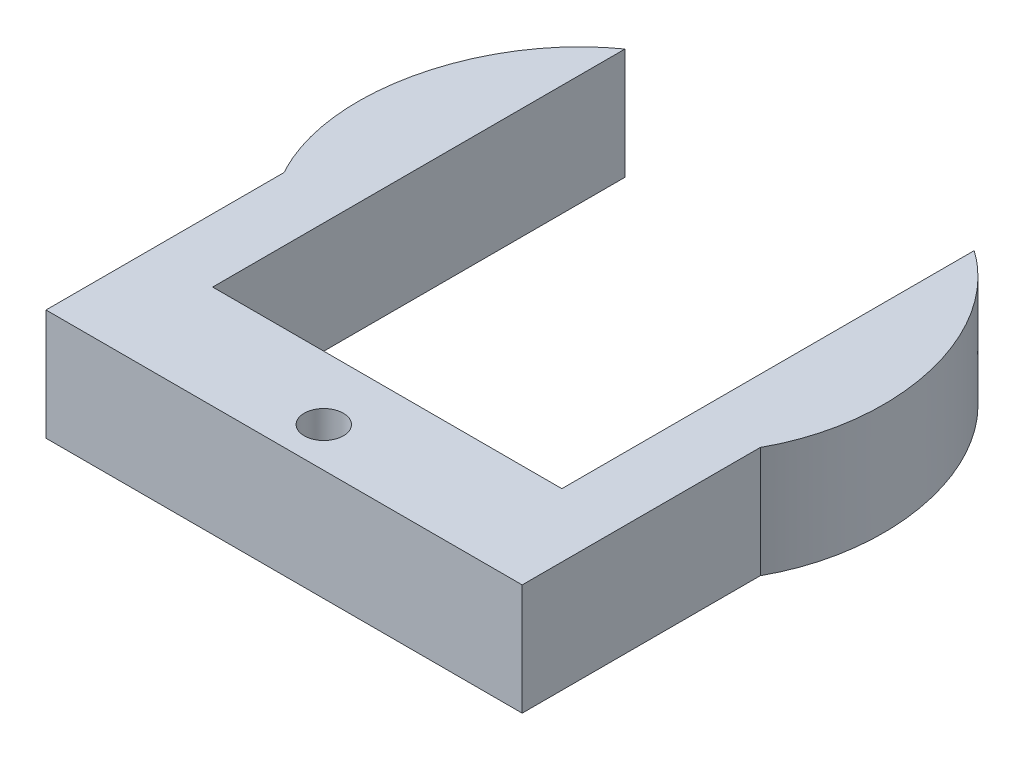
SolidWorks part; units mm, degrees
ref_plane "Front Plane" through (0, 0, 0) normal (0, 0, 1) x (1, 0, 0)
ref_plane "Top Plane" through (0, 0, 0) normal (0, 1, 0) x (1, 0, 0)
ref_plane "Right Plane" through (0, 0, 0) normal (1, 0, 0) x (0, 0, -1)
sketch "Sketch1" plane through (0, 0, 0) normal (0, 1, 0) x (1, 0, 0)
  line L0 (8, 67.5015) -> (8, 79.9541)
  line L1 (0, 15) -> (60, 15)
  line L3 (8, 28) -> (52, 28)
  line L4 (60, 15) -> (60, 28)
  line L8 (8, 28) -> (8, 67.5015)
  line L10 (60, 28) -> (60, 45)
  line L12 (52, 28) -> (52, 70.2973)
  line L13 (30, 28) -> (30, 82.123) construction
  line L14 (52, 70.2973) -> (52, 79.9541)
  line L15 (0, 15) -> (0, 45)
  arc A0 (11.5, 82) -> (0, 45) centre (24.25, 57.75) ccw construction
  spline S0 degree 3 poles (0, 45) (-4.2674, 52.7022) (-3.8497, 67.2321) (4.5722, 77.5249) (8, 79.9541) knots 0 0 0 0 0.616859 0.907352 0.907352 0.907352 0.907352
  spline S1 degree 3 poles (60, 45) (64.2674, 52.7022) (63.8497, 67.2321) (55.4278, 77.5249) (52, 79.9541) knots 0 0 0 0 0.616859 0.907352 0.907352 0.907352 0.907352
  dimension "D1" = 60
  dimension "D2" = 30
extrude "Boss-Extrude1" add sketch "Sketch1" along normal blind 14
sketch "Sketch3" plane through (0, 0, 0) normal (0, -1, 0) x (1, 0, 0)
  circle A0 centre (30, -20) radius 2.4697
extrude "Cut-Extrude1" cut sketch "Sketch3" against normal blind 21
